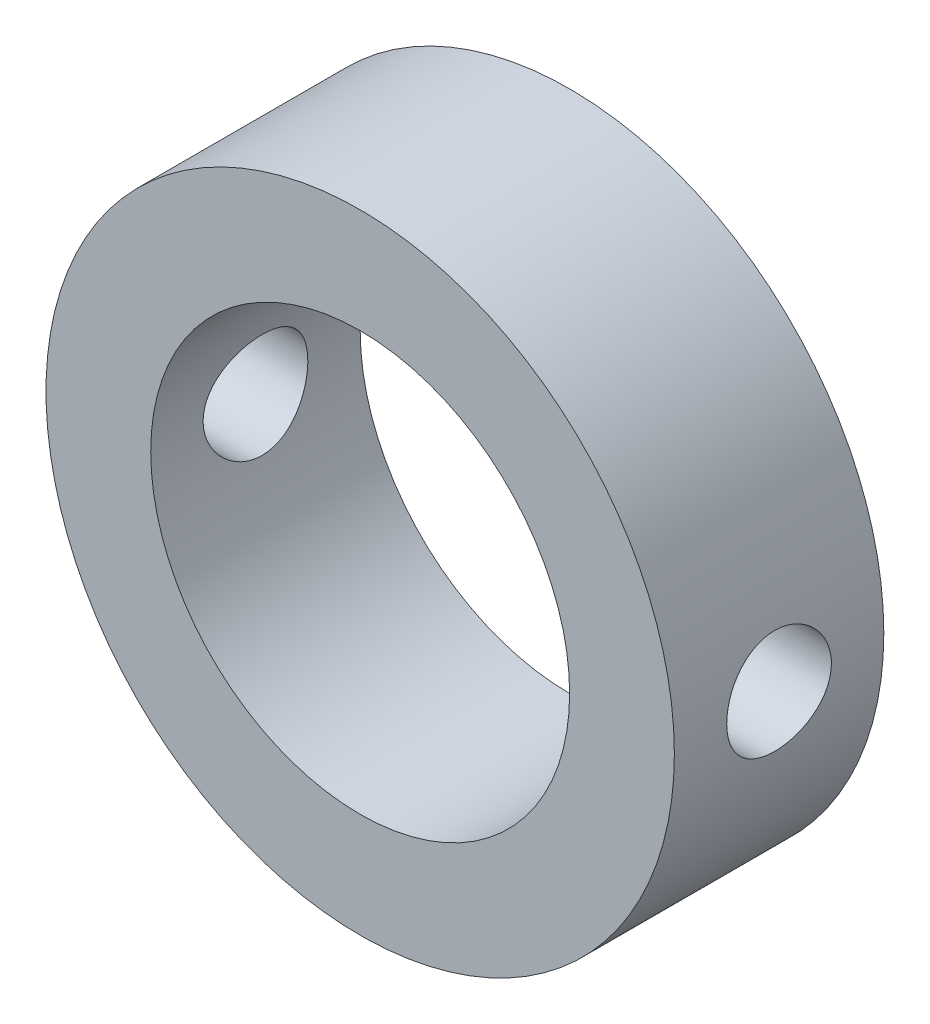
SolidWorks part; units mm, degrees
ref_plane "Front Plane" through (0, 0, 0) normal (0, 0, 1) x (1, 0, 0)
ref_plane "Top Plane" through (0, 0, 0) normal (0, 1, 0) x (1, 0, 0)
ref_plane "Right Plane" through (0, 0, 0) normal (1, 0, 0) x (0, 0, -1)
sketch "Sketch1" plane through (0, 0, 0) normal (0, 0, 1) x (1, 0, 0)
  circle A0 centre (0, 0) radius 8
  circle A1 centre (0, 0) radius 12
  dimension "D1" = 16
  dimension "D2" = 24
extrude "Boss-Extrude1" add sketch "Sketch1" along normal blind 8
sketch "Sketch2" plane through (0, 0, 0) normal (1, 0, 0) x (0, 0, -1)
  line L0 (-8, -12) -> (0, -12) construction
  circle A0 centre (-4, 0) radius 2
  dimension "D1" = 4
  dimension "D2" = 4
  dimension "D3" = 12
extrude "Cut-Extrude1" cut sketch "Sketch2" against normal mid plane 100
